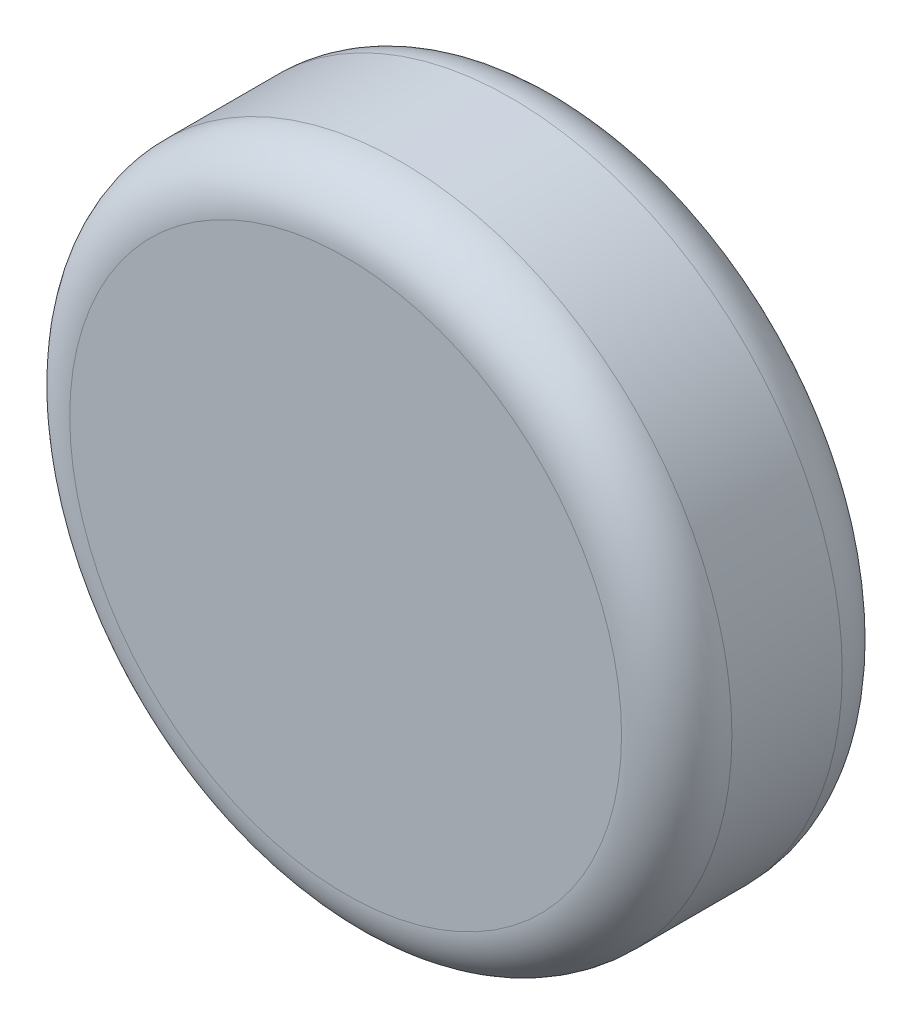
SolidWorks part; units mm, degrees
ref_plane "Plano frontal" through (0, 0, 0) normal (0, 0, 1) x (1, 0, 0)
ref_plane "Plano superior" through (0, 0, 0) normal (0, 1, 0) x (1, 0, 0)
ref_plane "Plano direito" through (0, 0, 0) normal (1, 0, 0) x (0, 0, -1)
sketch "Esboço1" plane through (0, 0, 0) normal (0, 0, 1) x (1, 0, 0)
  circle A0 centre (0, 0) radius 3
  dimension "D1" = 6
extrude "Ressalto-extrusão1" add sketch "Esboço1" along normal blind 2
fillet "Filete1" radius 0.5 2 edges at (3, 0, 0) (3, 0, 2)
